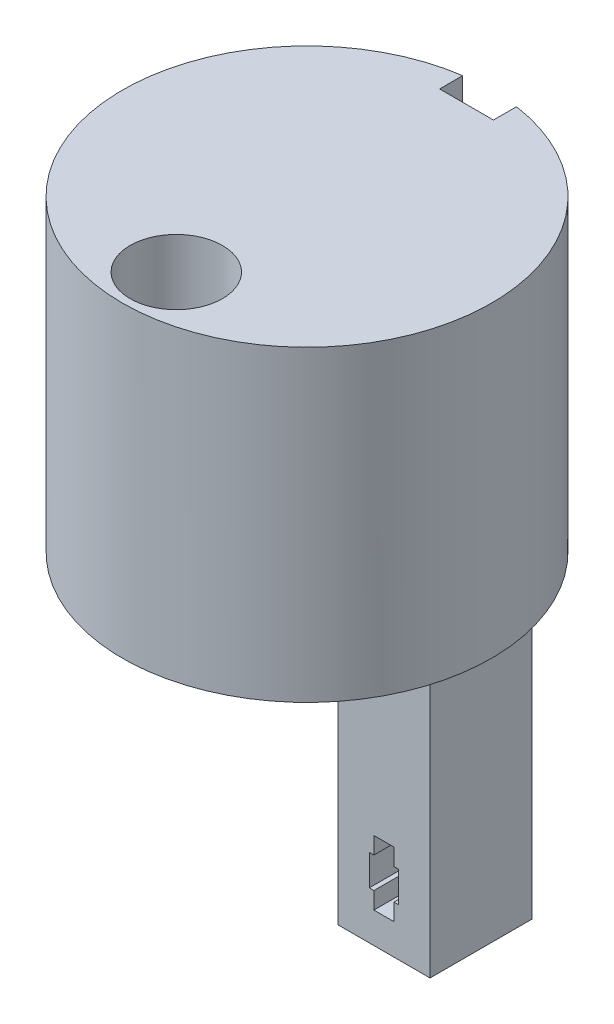
SolidWorks part; units mm, degrees
ref_plane "前视基准面" through (0, 0, 0) normal (0, 0, 1) x (1, 0, 0)
ref_plane "上视基准面" through (0, 0, 0) normal (0, 1, 0) x (1, 0, 0)
ref_plane "右视基准面" through (0, 0, 0) normal (1, 0, 0) x (0, 0, -1)
sketch "草图1" plane through (0, 0, 0) normal (0, 1, 0) x (1, 0, 0)
  circle A0 centre (0, 0) radius 12
  dimension "D1" = 24
extrude "凸台-拉伸1" add sketch "草图1" along normal blind 20
sketch "草图2" plane through (0, 0, 0) normal (0, -1, 0) x (1, 0, 0)
  line L0 (0, 0) -> (0, 7.9186) construction
  line L1 (0, 0) -> (7.5, 0) construction
  circle A0 centre (7.5, 0) radius 1.975
  circle A1 centre (-7.5, 0) radius 1.975
  dimension "D1" = 3.95
  dimension "D2" = 15
extrude "切除-拉伸1" cut sketch "草图2" against normal blind 15
sketch "草图3" plane through (0, 0, 0) normal (0, -1, 0) x (1, 0, 0)
  line L0 (0, 0) -> (0, 8.5) construction
  circle A0 centre (0, 8.5) radius 3
  point P4 (0, 6.7031)
  dimension "D1" = 6
  dimension "D2" = 8.5
extrude "切除-拉伸2" cut sketch "草图3" against normal through all
sketch "草图4" plane through (0, 0, 0) normal (0, -1, 0) x (1, 0, 0)
  line L0 (0, 0) -> (0, -12) construction
  line L2 (-3, -5) -> (3, -5)
  line L3 (-3, -5) -> (-3, -11.619)
  line L4 (-3, -11.619) -> (3, -11.619)
  line L5 (3, -5) -> (3, -11.619)
  line L6 (-3, -5) -> (3, -11.619) construction
  line L7 (-3, -11.619) -> (3, -5) construction
  circle A0 centre (0, 0) radius 12 construction
  circle A1 centre (0, 0) radius 12
  point P6 (0, -8.3095)
  circle M4 centre (0, 0) radius 12
  dimension "D1" = 7
  dimension "D2" = 6
extrude "凸台-拉伸2" add sketch "草图4" along normal blind 25 contours L5 L2 L3 L4 | L4 M4
sketch "草图5" plane through (0, 20, 0) normal (0, 1, 0) x (1, 0, 0)
  line L0 (0, 0) -> (0, 12) construction
  line L2 (1.75, 10.3717) -> (-1.75, 10.3717)
  line L3 (1.75, 10.3717) -> (1.75, 11.8717)
  line L4 (1.75, 11.8717) -> (-1.75, 11.8717)
  line L5 (-1.75, 10.3717) -> (-1.75, 11.8717)
  line L6 (1.75, 10.3717) -> (-1.75, 11.8717) construction
  line L7 (1.75, 11.8717) -> (-1.75, 10.3717) construction
  circle A0 centre (0, 0) radius 12 construction
  circle A1 centre (0, 0) radius 12
  point P5 (0, 11.1217)
  point P10 (-1.5, 10.9199)
  circle M4 centre (0, 0) radius 12
  dimension "D1" = 3.5
  dimension "D2" = 1.5
extrude "切除-拉伸3" cut sketch "草图5" against normal blind 37 contours L5 L2 L3 L4 | L4 M4
sketch "草图6" plane through (0, 0, -5) normal (0, 0, 1) x (1, 0, 0)
  line L0 (0, 0) -> (0, -20.9687) construction
  line L1 (-3, 0) -> (3, 0) construction
  line L2 (-3, -25) -> (3, -25) construction
  line L3 (-0.65, -23) -> (0.65, -23)
  line L4 (-0.65, -23) -> (-0.65, -18.8)
  line L5 (-0.65, -18.8) -> (0.65, -18.8)
  line L6 (0.65, -23) -> (0.65, -18.8)
  line L7 (-0.65, -23) -> (0.65, -18.8) construction
  line L8 (-0.65, -18.8) -> (0.65, -23) construction
  point P4 (0, -20.9)
  dimension "D1" = 1.3
  dimension "D2" = 4.2
  dimension "D3" = 2
extrude "切除-拉伸4" cut sketch "草图6" against normal blind 5 and the other way through all
sketch "草图7" plane through (0, 0, -10) normal (0, 0, 1) x (1, 0, 0)
  line L0 (0, -18.8) -> (0, -23) construction
  line L3 (0.65, -18.8) -> (0.65, -23) construction
  line L4 (-0.65, -23.5) -> (0.65, -23.5)
  line L5 (-0.65, -23.5) -> (-0.65, -18.3)
  line L6 (-0.65, -18.3) -> (0.65, -18.3)
  line L7 (0.65, -23.5) -> (0.65, -18.3)
  line L8 (-0.65, -23.5) -> (0.65, -18.3) construction
  line L9 (-0.65, -18.3) -> (0.65, -23.5) construction
  line L10 (0.65, -18.8) -> (0.65, -23) construction
  line L12 (0.65, -23) -> (-0.65, -23) construction
  line L13 (-0.65, -18.8) -> (0.65, -18.8) construction
  line L14 (0.65, -23) -> (-0.65, -23) construction
  line L15 (-0.65, -18.8) -> (0.65, -18.8) construction
  point P2 (0, 0)
  point P6 (0, -20.9)
  point P11 (0, 0)
  point P14 (0, 0)
  point P15 (0, 0)
  point P17 (0, -18.9)
  point P18 (0, 0)
  point P19 (0, -23)
  dimension "D1" = 5.2
extrude "切除-拉伸5" cut sketch "草图7" against normal through all
sketch "草图8" plane through (0, 0, -5) normal (0, 0, 1) x (1, 0, 0)
  line L0 (0, -18.8) -> (0, -23) construction
  line L2 (-0.95, -21.9) -> (0.95, -21.9)
  line L3 (-0.95, -21.9) -> (-0.95, -19.9)
  line L4 (0.65, -18.8) -> (-0.65, -18.8)
  line L5 (0.65, -23) -> (0.65, -18.8)
  line L6 (-0.65, -23) -> (0.65, -23)
  line L7 (-0.65, -18.8) -> (-0.65, -23)
  line L8 (0.65, -18.8) -> (-0.65, -18.8) construction
  line L9 (0.65, -23) -> (0.65, -18.8) construction
  line L10 (-0.65, -23) -> (0.65, -23) construction
  line L11 (-0.65, -18.8) -> (-0.65, -23) construction
  line L12 (-0.95, -19.9) -> (0.95, -19.9)
  line L13 (0.95, -21.9) -> (0.95, -19.9)
  line L14 (-0.95, -21.9) -> (0.95, -19.9) construction
  line L15 (-0.95, -19.9) -> (0.95, -21.9) construction
  point P6 (0, -20.9)
  dimension "D2" = 1.9
  dimension "D3" = 2
  dimension "D1" = 0
extrude "切除-拉伸6" cut sketch "草图8" against normal through all
chamfer "倒角1" distance 0.5 angle 45 2 edges at (7.5, 0, -1.975) (-7.5, 0, 1.975)
sketch "草图9" plane through (0, 0, 0) normal (0, -1, 0) x (1, 0, 0)
  line L0 (7.5, 0) -> (4.0258, 0) construction
  line L2 (4.5659, 0.4) -> (5.5659, 0.4)
  line L3 (4.5659, 0.4) -> (4.5659, -0.4)
  line L4 (4.5659, -0.4) -> (5.5659, -0.4)
  line L5 (5.5659, 0.4) -> (5.5659, -0.4)
  line L6 (4.5659, 0.4) -> (5.5659, -0.4) construction
  line L7 (4.5659, -0.4) -> (5.5659, 0.4) construction
  circle A1 centre (7.5, 0) radius 1.975
  circle A2 centre (7.5, 0) radius 1.975 construction
  point P0 (5.0659, 0)
  dimension "D2" = 1
  dimension "D3" = 0.8
  dimension "D1" = 0
extrude "切除-拉伸7" cut sketch "草图9" against normal up to surface (15 mm away) up to face at (7.5, 15, -1.975)
pattern_circular "阵列(圆周)1" count 8 over 360 about axis through (7.5, 0, 0) along (0, 1, 0) of "切除-拉伸7"
mirror "镜向1" about plane through (0, 0, 0) normal (1, 0, 0) of "阵列(圆周)1", "切除-拉伸7"
